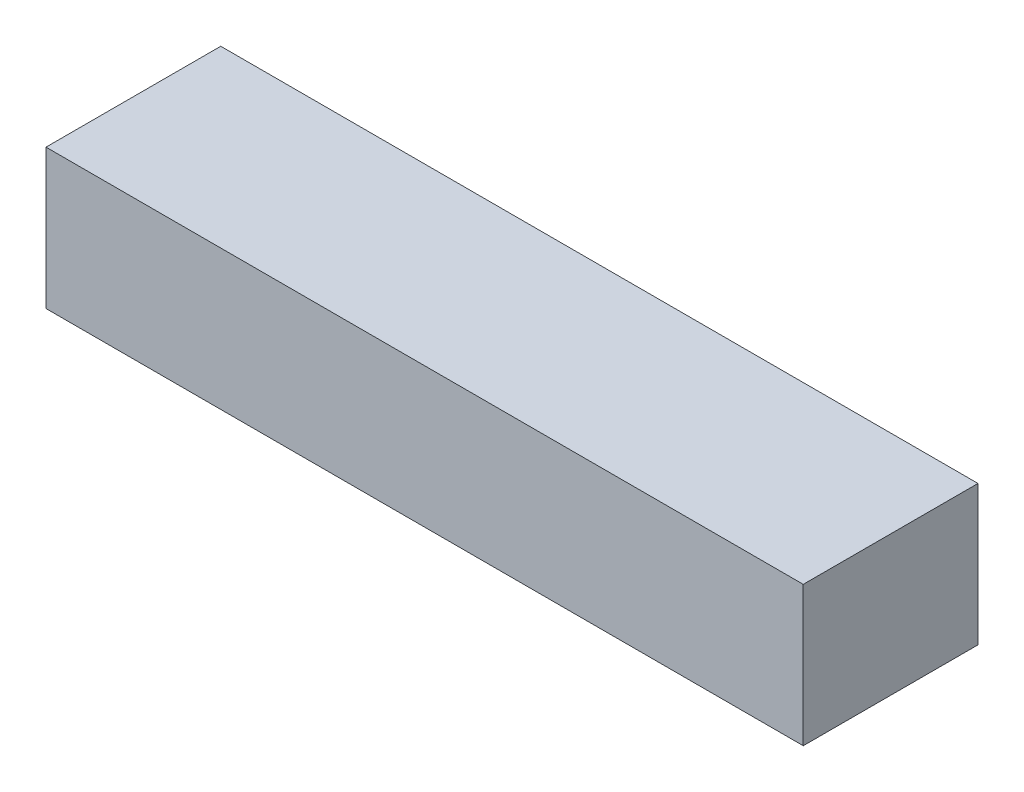
SolidWorks part; units mm, degrees
ref_plane "Front Plane" through (0, 0, 0) normal (0, 0, 1) x (1, 0, 0)
ref_plane "Top Plane" through (0, 0, 0) normal (0, 1, 0) x (1, 0, 0)
ref_plane "Right Plane" through (0, 0, 0) normal (1, 0, 0) x (0, 0, -1)
other "Configuration Table"
sketch "Sketch1" plane through (0, 0, 0) normal (0, 0, 1) x (1, 0, 0)
  line L1 (1078, 1624) -> (1208, 1624)
  line L2 (1078, 1624) -> (1078, 1648)
  line L3 (1078, 1648) -> (1208, 1648)
  line L4 (1208, 1624) -> (1208, 1648)
extrude "DET2_PLC_dilimi_1" add sketch "Sketch1" against normal blind 30 from offset 770 separate body
